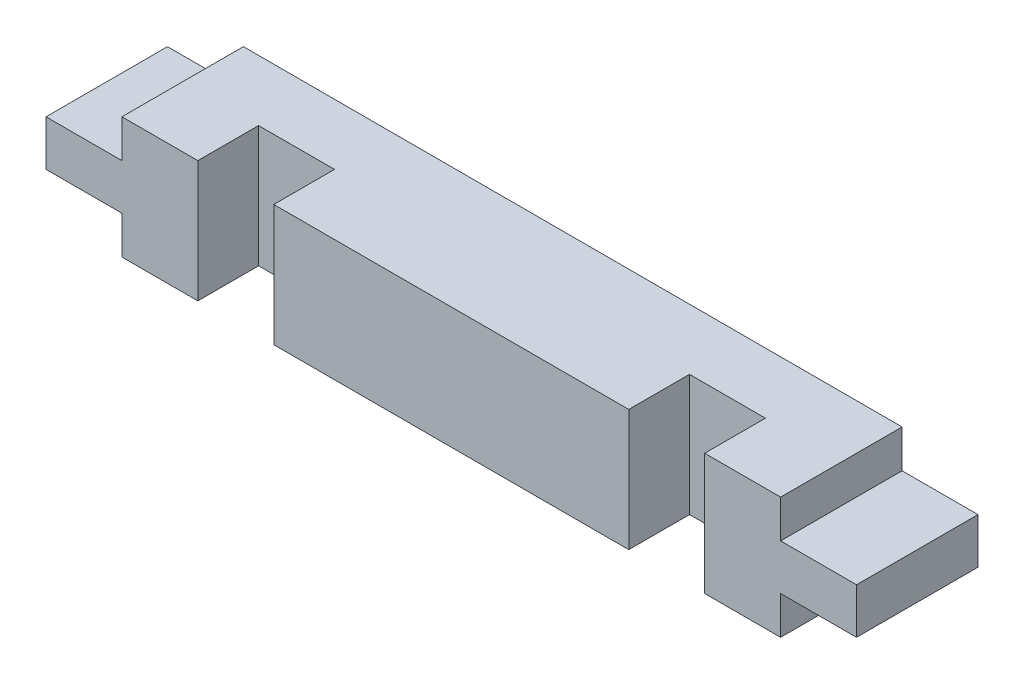
SolidWorks part; units mm, degrees
ref_plane "Front Plane" through (0, 0, 0) normal (0, 0, 1) x (1, 0, 0)
ref_plane "Top Plane" through (0, 0, 0) normal (0, 1, 0) x (1, 0, 0)
ref_plane "Right Plane" through (0, 0, 0) normal (1, 0, 0) x (0, 0, -1)
sketch "Sketch1" plane through (0, 0, 0) normal (0, 0, 1) x (1, 0, 0)
  line L0 (0, 0) -> (0, 3)
  line L1 (0, 3) -> (5, 3)
  line L2 (5, 3) -> (5, 5.5)
  line L3 (5, 5.5) -> (48.38, 5.5)
  line L4 (48.38, 5.5) -> (48.38, 3)
  line L5 (48.38, 3) -> (53.38, 3)
  line L6 (53.38, 3) -> (53.38, 0)
  line L7 (53.38, 0) -> (48.38, 0)
  line L8 (48.38, 0) -> (48.38, -2.5)
  line L9 (48.38, -2.5) -> (5, -2.5)
  line L10 (5, -2.5) -> (5, 0)
  line L11 (5, 0) -> (0, 0)
  dimension "D1" = 43.38
  dimension "D2" = 53.38
  dimension "D3" = 3
  dimension "D4" = 8
extrude "Boss-Extrude1" add sketch "Sketch1" along normal blind 8
sketch "Sketch2" plane through (0, 0, 8) normal (0, 0, 1) x (1, 0, 0)
  line L0 (5, -2.5) -> (48.38, -2.5) construction
  line L1 (10, -2.5) -> (15, -2.5)
  line L2 (10, -2.5) -> (10, 5.5)
  line L3 (10, 5.5) -> (15, 5.5)
  line L4 (15, -2.5) -> (15, 5.5)
  line L5 (48.38, 5.5) -> (5, 5.5) construction
  line L6 (38.38, -2.5) -> (43.38, -2.5)
  line L7 (38.38, -2.5) -> (38.38, 5.5)
  line L8 (38.38, 5.5) -> (43.38, 5.5)
  line L9 (43.38, -2.5) -> (43.38, 5.5)
  line L10 (5, 0) -> (5, -2.5) construction
  line L11 (48.38, -2.5) -> (48.38, 0) construction
  dimension "D1" = 5
  dimension "D2" = 5
  dimension "D3" = 5
extrude "Cut-Extrude1" cut sketch "Sketch2" against normal blind 4
